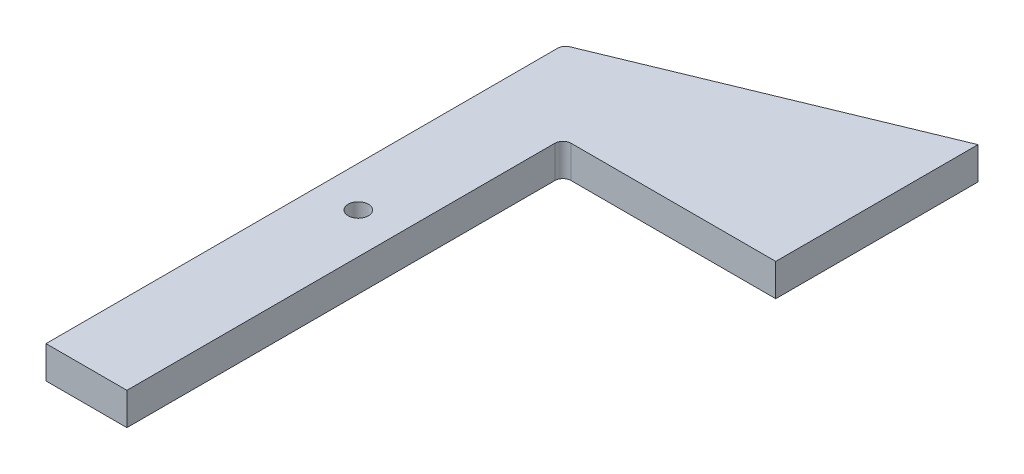
SolidWorks part; units mm, degrees
ref_plane "Front Plane" through (0, 0, 0) normal (0, 0, 1) x (1, 0, 0)
ref_plane "Top Plane" through (0, 0, 0) normal (0, 1, 0) x (1, 0, 0)
ref_plane "Right Plane" through (0, 0, 0) normal (1, 0, 0) x (0, 0, -1)
sketch "Sketch1" plane through (0, 0, 0) normal (0, 1, 0) x (1, 0, 0)
  line L0 (-50, 128.026) -> (42.202, 166.126)
  line L2 (-50, 128.026) -> (-50, -34.28)
  line L3 (-50, -34.28) -> (-24.6, -34.28)
  line L4 (-24.6, 102.626) -> (-24.6, -34.28)
  line L7 (-24.6, 102.626) -> (42.202, 102.626)
  line L8 (42.202, 128.026) -> (42.202, 102.626)
  line L10 (42.202, 128.026) -> (42.202, 166.126)
  dimension "D1" = 25.4
  dimension "D3" = 92.202
  dimension "D2" = 162.306
extrude "Boss-Extrude1" add sketch "Sketch1" along normal blind 10.16
sketch "Sketch2" plane through (0, 10.16, 0) normal (0, 1, 0) x (1, 0, 0)
  line L0 (-50, -34.28) -> (-24.6, -34.28) construction
  line L1 (-24.6, -34.28) -> (-24.6, 102.626) construction
  circle A0 centre (-37.3, 51.064) radius 3.175
  dimension "D1" = 6.35
  dimension "D2" = 85.344
  dimension "D3" = 12.7
extrude "Cut-Extrude1" cut sketch "Sketch2" against normal blind 10.16
fillet "Fillet1" radius 2.54 2 edges at (-24.6, 5.08, -102.626) (-50, 5.08, -128.026)
equation "\"t\"= 0.4in"
equation "\"D1@Sketch1\"=\"width\""
equation "\"width\"= 1in"
equation "\"D1@Boss-Extrude1\"=\"t\""
equation "\"D3@Sketch2\"=\"width\"/2"
equation "\"D1@Cut-Extrude1\"=\"t\""
